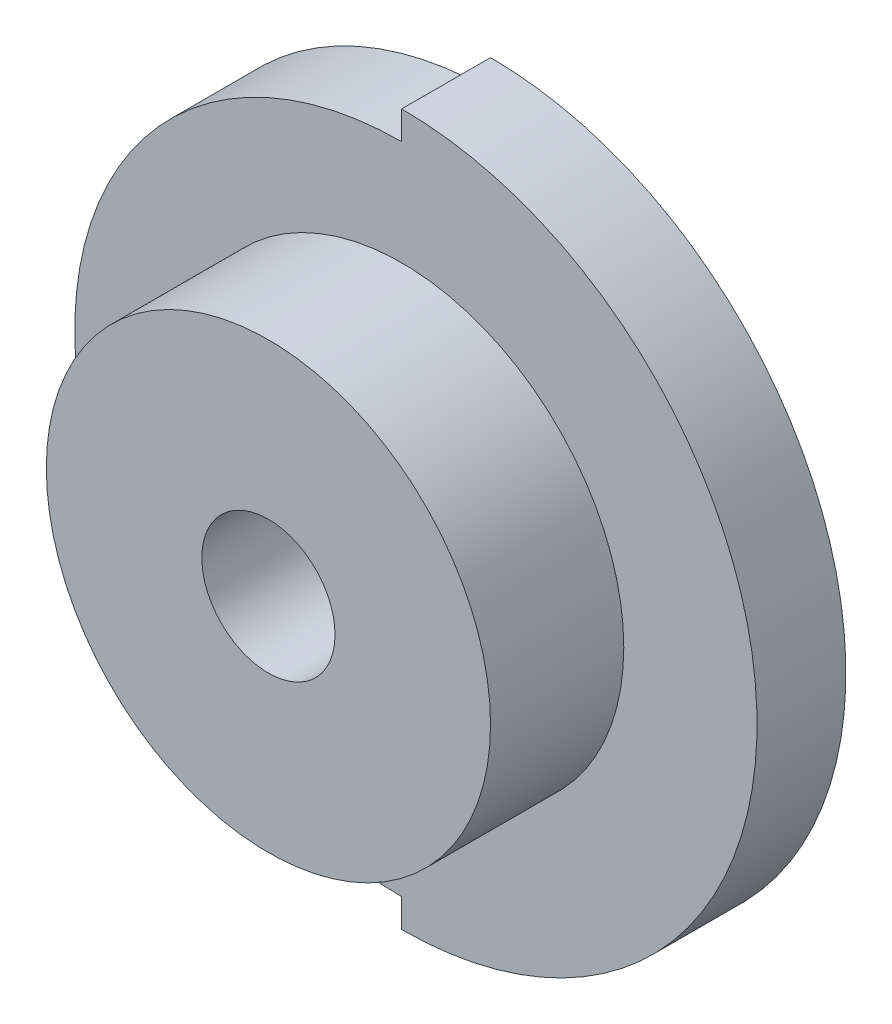
SolidWorks part; units mm, degrees
ref_plane "Front Plane" through (0, 0, 0) normal (0, 0, 1) x (1, 0, 0)
ref_plane "Top Plane" through (0, 0, 0) normal (0, 1, 0) x (1, 0, 0)
ref_plane "Right Plane" through (0, 0, 0) normal (1, 0, 0) x (0, 0, -1)
sketch "Sketch1" plane through (0, 0, 0) normal (0, 0, 1) x (1, 0, 0)
  circle A0 centre (0, 0) radius 25.4
  dimension "D1" = 50.8
extrude "Boss-Extrude1" add sketch "Sketch1" along normal blind 6.35
sketch "Sketch2" plane through (0, 0, 6.35) normal (0, 0, 1) x (1, 0, 0)
  circle A0 centre (0, 0) radius 15.875
  dimension "D1" = 31.75
extrude "Boss-Extrude2" add sketch "Sketch2" along normal blind 9.525
sketch "Sketch3" plane through (0, 0, 15.875) normal (0, 0, 1) x (1, 0, 0)
  circle A0 centre (0, 0) radius 4.7625
  dimension "D1" = 9.525
extrude "Cut-Extrude1" cut sketch "Sketch3" against normal up to surface (15.875 mm away) up to face at (25.4, 0, 0)
sketch "Sketch4" plane through (0, 0, 0) normal (0, 0, -1) x (-1, 0, 0)
  line L0 (0, 25.4) -> (0, 23.368)
  line L1 (0, -23.368) -> (0, -25.4)
  arc A0 (0, -23.368) -> (0, 23.368) centre (0, 0) ccw
  circle A1 centre (0, 0) radius 25.4 construction
  arc A2 (0, -25.4) -> (0, 25.4) centre (0, 0) ccw
  dimension "D1" = 46.736
extrude "Cut-Extrude2" cut sketch "Sketch4" against normal up to surface (6.35 mm away) up to face at (25.4, 0, 6.35)
